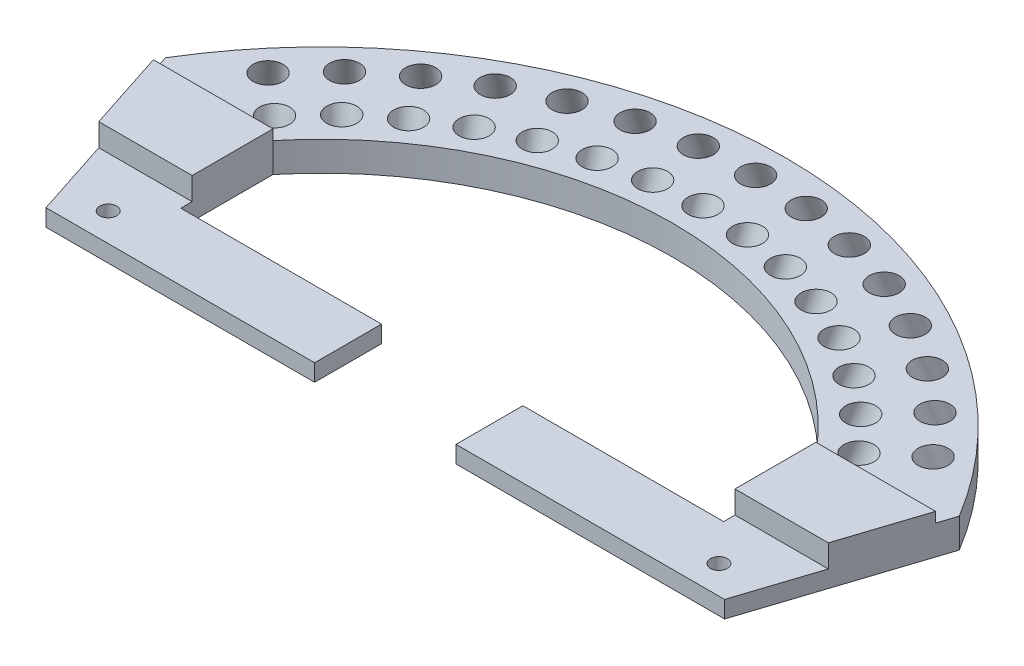
SolidWorks part; units mm, degrees
ref_plane "Front Plane" through (0, 0, 0) normal (0, 0, 1) x (1, 0, 0)
ref_plane "Top Plane" through (0, 0, 0) normal (0, 1, 0) x (1, 0, 0)
ref_plane "Right Plane" through (0, 0, 0) normal (1, 0, 0) x (0, 0, -1)
sketch "Sketch1" plane through (0, 0, 0) normal (0, 1, 0) x (1, 0, 0)
  line L0 (0, 0) -> (0, 31.147) construction
  line L1 (-60, -40) -> (60, -40) construction
  line L2 (-60, -40) -> (-60, 40) construction
  line L3 (-60, 40) -> (60, 40) construction
  line L4 (60, -40) -> (60, 40) construction
  line L5 (-60, -40) -> (60, 40) construction
  line L6 (-60, 40) -> (60, -40) construction
  line L7 (48, 23.11) -> (48, 9.16)
  line L8 (-60, 23.11) -> (-48, 23.11)
  line L9 (-60, 23.11) -> (-60, 9.16)
  line L10 (-60, 9.16) -> (-48, 9.16)
  line L11 (-48, 23.11) -> (-48, 9.16)
  line L12 (60, 9.16) -> (48, 9.16)
  line L13 (60, 23.11) -> (60, 9.16)
  line L14 (60, 23.11) -> (48, 23.11)
  line L15 (-47.5161, 40) -> (47.5161, 40)
  line L16 (60, 11.27) -> (-60, 11.27)
  line L17 (-60, 11.27) -> (-70.1997, 42.5937)
  line L18 (60, 11.27) -> (70.1997, 42.5937)
  line L19 (48, 23.11) -> (48, 39.418)
  line L20 (-48, 23.11) -> (-48, 39.418)
  line L21 (48, 23.11) -> (-48, 23.11)
  circle A0 centre (-54, 16.27) radius 1.5
  circle A1 centre (-54, -16.28) radius 1.5 construction
  circle A2 centre (54, -16.28) radius 1.5 construction
  circle A3 centre (54, 16.27) radius 1.5
  circle A4 centre (0, 0) radius 72.111 construction
  circle A5 centre (0, 0) radius 62.111
  circle A6 centre (0, 0) radius 82.111
  point P0 (0, 0)
  dimension "D5" = 3
  dimension "D6" = 3
  dimension "D7" = 10
  dimension "D8" = 10
  dimension "D1" = 80
  dimension "D2" = 120
  dimension "D3" = 23.73
  dimension "D4" = 32.55
  dimension "D9" = 12
  dimension "D10" = 6
  dimension "D11" = 7.11
  dimension "D12" = 6.84
  dimension "D13" = 5
extrude "Boss-Extrude1" add sketch "Sketch1" along normal blind 3
sketch "Sketch2" plane through (0, 3, 0) normal (0, 1, 0) x (1, 0, 0)
  line L2 (-48, 39.418) -> (48, 39.418) construction
  line L4 (48, 23.11) -> (48, 39.418) construction
  line L5 (-88.4384, 39.418) -> (88.4384, 39.418)
  circle A0 centre (0, 0) radius 62.111
  circle A1 centre (0, 0) radius 82.3372
  point P15 (0, 39.418)
extrude "Boss-Extrude2" add sketch "Sketch2" along normal blind 2.2
sketch "Sketch3" plane through (0, 3, 0) normal (0, 1, 0) x (1, 0, 0)
  line L0 (-64.5066, 25.11) -> (64.5066, 25.11)
  line L1 (-60, 11.27) -> (-69.1657, 39.418) construction
  line L2 (60, 11.27) -> (69.1657, 39.418) construction
  line L3 (64.5066, 25.11) -> (69.1657, 39.418)
  line L6 (-48, 39.418) -> (-48, 25.11)
  line L8 (48, 25.11) -> (48, 39.418)
  line L9 (48, 23.11) -> (-48, 23.11) construction
  line L10 (48, 23.11) -> (48, 39.418) construction
  line L11 (-48, 23.11) -> (-48, 39.418) construction
  line L12 (-69.1657, 39.418) -> (-64.5066, 25.11)
  line L13 (48, 39.418) -> (-48, 39.418) construction
  line L14 (-69.1657, 39.418) -> (69.1657, 39.418)
  circle A0 centre (0, 0) radius 62.111
  point P36 (0, 39.418)
  dimension "D1" = 2
extrude "Boss-Extrude3" add sketch "Sketch3" along normal blind 4
sketch "Sketch4" plane through (0, 5.2, 0) normal (0, -1, 0) x (1, 0, 0)
  line L0 (0, -62.111) -> (0, -82.111) construction
  line L1 (-4.3078, -72.111) -> (4.3078, -72.111) construction
  line L2 (0, -74.111) -> (0, -70.111) construction
  line L3 (0, 0) -> (-55.7281, -45.7644) construction
  line L4 (0, 0) -> (0, -48.9342) construction
  circle A1 centre (0, 0) radius 62.111
  circle A2 centre (0, 0) radius 82.111
  circle A3 centre (0, -67.461) radius 2.65
  circle A4 centre (0, -76.761) radius 2.65
  circle A5 centre (0, 0) radius 72.111 construction
  point P18 (0, -72.111)
  point P42 (0, 0)
  point P52 (0, 0)
  point P81 (0, 0)
  dimension "D1" = 5.3
  dimension "D2" = 9.3
  dimension "D3" = 50.607
  dimension "D5" = 10
  dimension "D4" = 20
ref_plane "Plane1" through (0, 0, 0) normal (-1, 0, 0) x (0, 0, 1)
sketch3d "3DSketch1" [suppressed]
  line L0 (0, 5.2, -72.111) -> (0, 20.2, -72.111) construction
  line L1 (0, 20.2, -72.111) -> (0, -33.0638, -81.5029) construction
  line L2 (0, 20.2, -72.111) -> (0, -36.8854, -62.0453) construction
  line L3 (0, 0, 0) -> (0, 5.2, -72.111) construction
  line L32 (0, 0, 0) -> (0, 15, 0)
  circle A0 centre (0, 0, 0) radius 72.2983 construction
  circle A1 centre (0, 5.2, -72.111) radius 4.11
  point P7 (0, 72.111, 5.2)
  point P20 (0, 9.2992, -71.8127)
  dimension "D1" = 15
  dimension "D2" = 10
  dimension "D3" = 10
sketch3d "3DSketch2"
  line L0 (0, 0, 0) -> (0, 20.5578, 0) construction
  line L1 (0, 5.2, -100.5185) -> (0, 5.2, 0) construction
  line L2 (0, 5.2, 0) -> (0, 0, 0) construction
  line L3 (0, 7, -72.111) -> (0, 22, -72.111) construction
  line L4 (0, 5.2, -72.111) -> (0, 7, -72.111) construction
  line L5 (0, 22, -72.111) -> (0, 5.2, -65.9963) construction
  line L6 (0, 7, 0) -> (0, 7, -100) construction
  line L7 (0, 22, -72.111) -> (0, 5.2, -78.2257) construction
  line L8 (0, -27.6892, -55.4903) -> (0, 38.0892, -79.4317) construction
  line L9 (0, -27.6892, -88.7317) -> (0, 38.0892, -64.7903) construction
  line L10 (-0.0436, -37.0862, -49.5705) -> (-0.0436, 47.4862, -80.3523)
  line L11 (0, -27.6892, -57.9903) -> (0, 38.0892, -81.9317)
  line L12 (0, -37.0862, -94.6189) -> (0, 47.4862, -63.837)
  line L13 (0, -27.6892, -86.2317) -> (0, 38.0892, -62.2903)
  circle A0 centre (0, 5.2, -67.461) radius 2.5
  circle A1 centre (0, 5.2, -76.761) radius 2.5
  circle A2 centre (0, 5.2, 0) radius 62.111 construction
  circle A3 centre (0, 5.2, 0) radius 82.111 construction
  circle A4 centre (0, 5.2, 0) radius 72.111 construction
  point P9 (0, 7.7, -67.461)
  point P12 (0, 7.7, -76.761)
  point P14 (0, 67.311, 0)
  point P17 (0, 87.311, 0)
  point P20 (0, 77.311, 0)
  point P21 (0, 5.2, -72.111)
  point P34 (0, 5.2, -67.461)
  point P37 (0, 5.2, -76.761)
  point P38 (-0.0436, 5.2, -64.9614)
  point P41 (0, 5.2, -69.961)
  point P44 (0, 5.2, -79.228)
  point P47 (0, 5.2, -74.261)
  dimension "D1" = 5
  dimension "D2" = 5
  dimension "D3" = 9.3
  dimension "D4" = 20
  dimension "D5" = 10
  dimension "D6" = 4.65
  dimension "D7" = 1.8
  dimension "D8" = 15
  dimension "D9" = 20
  dimension "D10" = 20
extrude "Cut-Extrude2" cut sketch "Sketch4" along direction (0, 0.9397, -0.342) on the side of the normal blind 15.2 contours A3
sketch "Sketch6" plane through (0, 5.2, 0) normal (0, 1, 0) x (1, 0, 0)
  line L0 (0, 13.0181) -> (0, -13.0181)
  line L1 (16.8951, 0) -> (-16.8951, 0)
  point P4 (0, 0)
  point P7 (0, 0)
sketch "Sketch7" plane through (0, 5.2, 0) normal (0, 1, 0) x (1, 0, 0)
  line L0 (0, 0) -> (0, 100) construction
  circle A0 centre (0, 67.461) radius 2.65
  circle A1 centre (0, 76.761) radius 2.65
  circle A2 centre (0, 0) radius 82.111 construction
  circle A3 centre (0, 0) radius 62.111 construction
  circle A4 centre (0, 0) radius 72.111 construction
  dimension "D1" = 5.3
  dimension "D3" = 4.65
  dimension "D2" = 9.3
extrude "Cut-Extrude3" cut sketch "Sketch7" along direction (0, 0.9397, 0.342) on the side against the normal blind 13.5 contours L0 A1 | A1 L0
pattern_circular "CirPattern1" count 8 every 7.143 of "Cut-Extrude2"
pattern_circular "CirPattern2" count 8 every 7.143 of "Cut-Extrude2"
pattern_circular "CirPattern3" count 8 every 7.143 of "Cut-Extrude3"
pattern_circular "CirPattern4" count 8 every 7.143 of "Cut-Extrude3"
sketch "Sketch8" plane through (0, 0, 0) normal (0, -1, 0) x (1, 0, 0)
  line L0 (-60, -11.27) -> (60, -11.27) construction
  line L1 (0, -29.2252) -> (0, 6.6852) construction
  line L3 (-12.5, 4.4738) -> (12.5, 4.4738)
  line L4 (-12.5, 4.4738) -> (-12.5, -27.0138)
  line L5 (-12.5, -27.0138) -> (12.5, -27.0138)
  line L6 (12.5, 4.4738) -> (12.5, -27.0138)
  line L7 (-12.5, 4.4738) -> (12.5, -27.0138) construction
  line L8 (-12.5, -27.0138) -> (12.5, 4.4738) construction
  point P4 (0, -11.27)
  point P8 (0, -11.27)
  dimension "D1" = 25
extrude "Cut-Extrude4" cut sketch "Sketch8" against normal up to surface (3 mm away)
